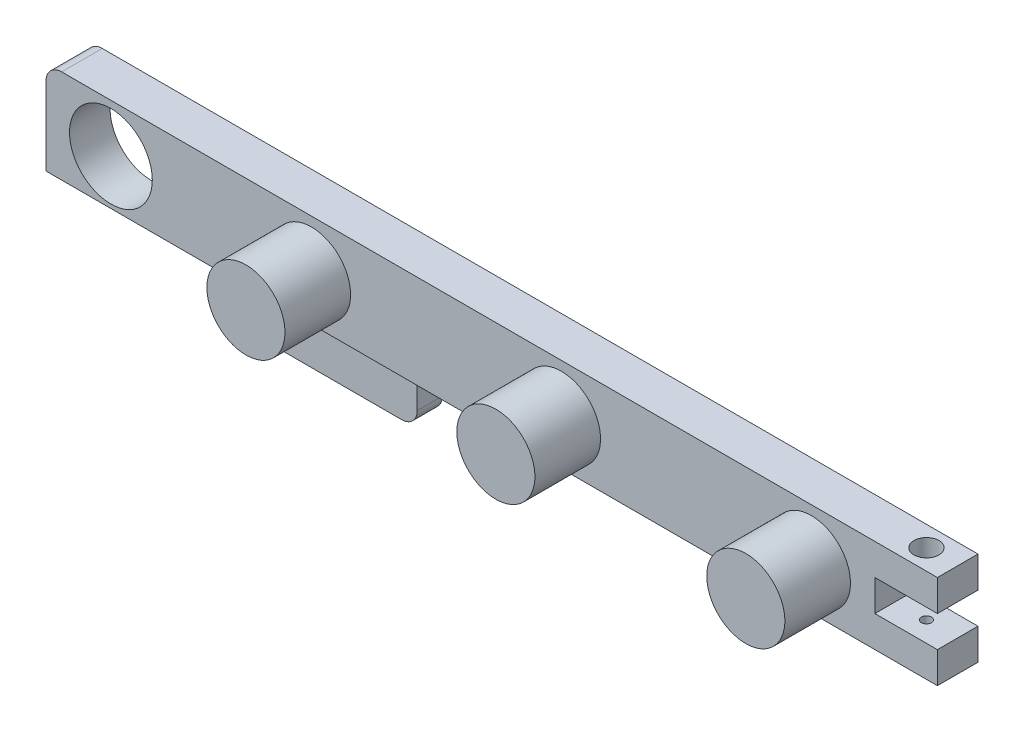
SolidWorks part; units mm, degrees
ref_plane "Front Plane" through (0, 0, 0) normal (0, 0, 1) x (1, 0, 0)
ref_plane "Top Plane" through (0, 0, 0) normal (0, 1, 0) x (1, 0, 0)
ref_plane "Right Plane" through (0, 0, 0) normal (1, 0, 0) x (0, 0, -1)
sketch "Sketch1" plane through (0, 0, 0) normal (0, 0, 1) x (1, 0, 0)
  line L1 (0, 0) -> (355.325, 0)
  line L2 (0, 0) -> (0, 30)
  line L3 (0, 30) -> (355.325, 30)
  line L4 (355.325, 0) -> (355.325, 30)
  line L5 (50, 0) -> (250, 0)
  line L6 (50, 0) -> (50, -17)
  line L7 (50, -17) -> (250, -17)
  line L8 (250, 0) -> (250, -17)
  line L9 (0, 0) -> (355.325, 0)
  line L10 (0, 0) -> (0, -17)
  line L11 (0, -17) -> (355.325, -17)
  line L12 (355.325, 0) -> (355.325, -17)
  line L13 (0, 0) -> (177.6625, 0)
  line L14 (0, 0) -> (0, -17)
  line L15 (0, -17) -> (177.6625, -17)
  line L16 (177.6625, 0) -> (177.6625, -17)
  line L17 (0, 0) -> (50, 0)
  line L18 (0, 0) -> (0, -5)
  line L19 (0, -5) -> (50, -5)
  line L20 (50, 0) -> (50, -5)
  circle A0 centre (20.775, 14.5) radius 12.5
  circle A1 centre (334.55, 14.5) radius 12.5
  circle A2 centre (60, -2.5) radius 1
  circle A3 centre (68, -2.5) radius 1
  circle A4 centre (60, -14.5) radius 1
  circle A5 centre (68, -14.5) radius 1
  dimension "D1" = 25
  dimension "D11" = 2
  dimension "D2" = 313.775
  dimension "D3" = 20.775
  dimension "D4" = 20.775
  dimension "D5" = 30
  dimension "D6" = 15.5
  dimension "D7" = 15.5
  dimension "D8" = 17
  dimension "D9" = 50
  dimension "D10" = 200
  dimension "D12" = 8
  dimension "D13" = 12
  dimension "D14" = 8
  dimension "D15" = 12
  dimension "D16" = 10
  dimension "D17" = 10
  dimension "D18" = 2.5
  dimension "D19" = 2.5
  dimension "D20" = 5
extrude "Boss-Extrude3" add sketch "Sketch1" along normal blind 13 contours L1 L9 L4 L3 L2 A1 A0 | L16 L1 L6 L7 A5 A4 A3 A2 | L10 L19 L6 L1
fillet "Fillet3" radius 5 6 edges at (355.325, 0, 6.5) (355.325, 30, 6.5) (177.6625, -17, 6.5) (50, -17, 6.5) (0, -5, 6.5) (0, 30, 6.5)
sketch "Sketch3" plane through (0, 0, 13) normal (0, 0, 1) x (1, 0, 0)
  line L0 (0, 0) -> (0, 25) construction
  circle A0 centre (85, 14.5) radius 12.5
  circle A1 centre (165, 14.5) radius 12.5
  circle A2 centre (245, 14.5) radius 12.5
  dimension "D1" = 25
  dimension "D2" = 85
  dimension "D3" = 80
  dimension "D4" = 80
extrude "Boss-Extrude4" add sketch "Sketch3" along normal blind 13
sketch "Sketch4" plane through (0, 0, 0) normal (0, 0, -1) x (-1, 0, 0)
  circle A0 centre (-68, -2.5) radius 1.425
  circle A1 centre (-60, -2.5) radius 1.425
  circle A2 centre (-60, -14.5) radius 1.425
  circle A3 centre (-68, -14.5) radius 1.425
  dimension "D1" = 2.85
extrude "Cut-Extrude1" cut sketch "Sketch4" against normal up to next
sketch "Sketch5" plane through (0, 0, 0) normal (0, 0, -1) x (-1, 0, 0)
  line L1 (-177.6625, 0) -> (-113.8325, 0)
  line L2 (-177.6625, 0) -> (-177.6625, -18)
  line L3 (-177.6625, -18) -> (-113.8325, -18)
  line L4 (-113.8325, 0) -> (-113.8325, -18)
  dimension "D1" = 63.83
  dimension "D2" = 18
extrude "Cut-Extrude3" cut sketch "Sketch5" against normal through all
fillet "Fillet4" radius 5 1 edges at (113.8325, -17, 6.5)
sketch "Sketch6" plane through (0, 0, 13) normal (0, 0, 1) x (1, 0, 0)
  line L1 (50, 0) -> (113.8325, 0)
  line L2 (50, 0) -> (50, -17)
  line L3 (50, -17) -> (113.8325, -17)
  line L4 (113.8325, 0) -> (113.8325, -17)
extrude "Cut-Extrude4" cut sketch "Sketch6" against normal blind 5
sketch "Sketch7" plane through (0, 0, 8) normal (0, 0, 1) x (1, 0, 0)
  circle A0 centre (60, -2.5) radius 1
  circle A1 centre (68, -2.5) radius 1
  circle A2 centre (68, -14.5) radius 1
  circle A3 centre (60, -14.5) radius 1
  circle A4 centre (60, -14.5) radius 2.1596
  circle A5 centre (60, -2.5) radius 2.1171
  circle A6 centre (68, -2.5) radius 1.9161
  circle A7 centre (68, -14.5) radius 2.4159
  dimension "D1" = 2
extrude "Boss-Extrude5" add sketch "Sketch7" against normal blind 8
sketch "Sketch8" plane through (0, 0, 26) normal (0, 0, 1) x (1, 0, 0)
  circle A0 centre (85, 14.5) radius 12.5
  circle A1 centre (165, 14.5) radius 12.5
  circle A2 centre (245, 14.5) radius 12.5
extrude "Boss-Extrude6" add sketch "Sketch8" along normal blind 13
sketch "Sketch10" plane through (0, 0, 13) normal (0, 0, 1) x (1, 0, 0)
  line L0 (50, 0) -> (350.325, 0) construction
  line L1 (355.325, 30) -> (285.325, 30)
  line L2 (355.325, 30) -> (355.325, 0)
  line L3 (355.325, 0) -> (285.325, 0)
  line L4 (285.325, 30) -> (285.325, 0)
  line L5 (5, 30) -> (350.325, 30) construction
  line L6 (285.325, 20) -> (265.325, 20)
  line L7 (285.325, 20) -> (285.325, 10)
  line L8 (285.325, 10) -> (265.325, 10)
  line L9 (265.325, 20) -> (265.325, 10)
  line L10 (355.325, 5) -> (355.325, 25) construction
  line M5 (50, 0) -> (350.325, 0)
  arc M6 (350.325, 0) -> (355.325, 5) centre (350.325, 5) ccw
  line M7 (355.325, 5) -> (355.325, 25)
  arc M8 (355.325, 25) -> (350.325, 30) centre (350.325, 25) ccw
  line M9 (350.325, 30) -> (5, 30)
  circle M17 centre (334.55, 14.5) radius 12.5
  dimension "D1" = 70
  dimension "D2" = 20
  dimension "D3" = 10
  dimension "D4" = 10
extrude "Cut-Extrude6" cut sketch "Sketch10" against normal through all contours L6 L9 L8 L4 | L4 M9 M5 M6 M7 M8 M17
sketch "Sketch11" plane through (0, 0, 13) normal (0, 0, 1) x (1, 0, 0)
  circle A0 centre (20.775, 14.5) radius 13.25
  dimension "D1" = 26.5
extrude "Cut-Extrude7" cut sketch "Sketch11" against normal through all
sketch "Sketch12" plane through (0, 0, 8) normal (0, 0, 1) x (1, 0, 0)
  circle A0 centre (60, -2.5) radius 1.25
  circle A1 centre (68, -2.5) radius 1.25
  circle A2 centre (68, -14.5) radius 1.25
  circle A3 centre (60, -14.5) radius 1.25
  dimension "D1" = 2.5
extrude "Cut-Extrude8" cut sketch "Sketch12" against normal through all
sketch "Sketch15" plane through (0, 30, 0) normal (0, 1, 0) x (1, 0, 0)
  line L1 (5, 0) -> (285.325, 0) construction
  line L2 (285.325, 0) -> (285.325, -13) construction
  circle A0 centre (275.325, -6.5) radius 1.6
  dimension "D1" = 3.2
  dimension "D2" = 6.5
  dimension "D3" = 10
extrude "Cut-Extrude10" cut sketch "Sketch15" against normal through all
sketch "Sketch17" plane through (0, 30, 0) normal (0, 1, 0) x (1, 0, 0)
  circle A0 centre (275.325, -6.5) radius 4
  dimension "D1" = 8
extrude "Cut-Extrude11" cut sketch "Sketch17" against normal blind 7.5
sketch "Sketch18" plane through (0, 0, 0) normal (0, -1, 0) x (1, 0, 0)
  circle A0 centre (275.325, 6.5) radius 4.25
  dimension "D1" = 8.5
extrude "Cut-Extrude12" cut sketch "Sketch18" against normal blind 7.5
sketch "Sketch19" plane through (0, 0, 13) normal (0, 0, 1) x (1, 0, 0)
  line L1 (50, 0) -> (-2.5375, 0)
  line L2 (50, 0) -> (50, -17.902)
  line L3 (50, -17.902) -> (-2.5375, -17.902)
  line L4 (-2.5375, 0) -> (-2.5375, -17.902)
extrude "Cut-Extrude13" cut sketch "Sketch19" against normal blind 5
sketch "Sketch20" plane through (0, 0, 39) normal (0, 0, 1) x (1, 0, 0)
  circle A0 centre (85, 14.5) radius 12.5
  circle A1 centre (165, 14.5) radius 12.5
  circle A2 centre (245, 14.5) radius 12.5
extrude "Cut-Extrude14" cut sketch "Sketch20" against normal blind 5
